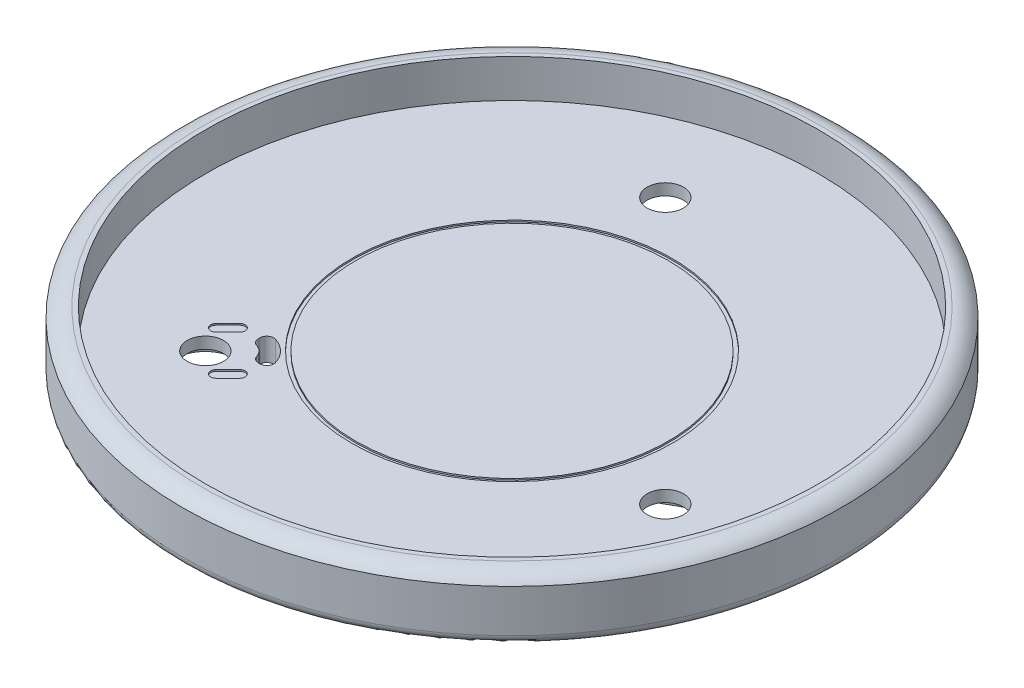
SolidWorks part; units mm, degrees
ref_plane "前视基准面" through (0, 0, 0) normal (0, 0, 1) x (1, 0, 0)
ref_plane "上视基准面" through (0, 0, 0) normal (0, 1, 0) x (1, 0, 0)
ref_plane "右视基准面" through (0, 0, 0) normal (1, 0, 0) x (0, 0, -1)
sketch "草图1" plane through (0, 0, 0) normal (0, 1, 0) x (1, 0, 0)
  circle A0 centre (0, 0) radius 40.2
  circle A1 centre (0, 0) radius 20.5 construction
  dimension "D1" = 80.4
  dimension "D2" = 41
extrude "凸台-拉伸1" add sketch "草图1" along normal blind 3
sketch "草图3" plane through (0, 0, 0) normal (0, -1, 0) x (1, 0, 0)
  circle A0 centre (0, 0) radius 43.2
  circle A1 centre (0, 0) radius 40.2 construction
  circle A2 centre (0, 0) radius 40.2
  dimension "D1" = 3
extrude "凸台-拉伸2" add sketch "草图3" against normal blind 8
sketch "草图4" plane through (0, 3, 0) normal (0, 1, 0) x (1, 0, 0)
  line L0 (-37.8336, 0) -> (34.4444, 0) construction
  line L1 (0, 37.4001) -> (0, -32.3556) construction
  circle A0 centre (0, 0) radius 20.5
  circle A1 centre (0, 0) radius 21
  dimension "D1" = 41
  dimension "D2" = 42
extrude "切除-拉伸1" cut sketch "草图4" against normal blind 0.2
sketch "草图5" plane through (0, 0, 0) normal (1, 0, 0) x (0, 0, -1)
  line L0 (43.2, 6.8) -> (43.2, 8)
  line L2 (43.2, 8) -> (40.8, 8)
  line L3 (40.2, 8) -> (-40.2, 8) construction
  line L4 (0, 0) -> (0, 12.9368)
  arc A0 (40.8, 8) -> (43.2, 6.8) centre (40.8, 5) cw
  dimension "D1" = 1.2
  dimension "D2" = 2.4
revolve "切除-旋转1" cut sketch "草图5" angle 360 about L4
fillet "圆角2" radius 1.2 1 edges at (0, 0, -43.2)
sketch "草图6" plane through (0, 0, 0) normal (0, -1, 0) x (1, 0, 0)
  line L0 (-29.5028, 0) -> (27.9284, 0) construction
  line L1 (0, 23.6501) -> (0, -22.1442) construction
  line L2 (-26, 23.2) -> (-23.8509, 18.3731)
  line L3 (-24, 26) -> (-18, 26)
  line L4 (-26, 24) -> (-26, 19)
  line L5 (-20.1967, 16) -> (-18, 16)
  line L6 (-16, 20.1967) -> (-16, 18)
  line L7 (-23.2, 26) -> (-18.3731, 23.8509)
  line L8 (33.0918, 10.9167) -> (27.837, 11.469)
  line L9 (33.7846, 10.5167) -> (29.4545, 13.0167)
  line L10 (34.5167, 7.7846) -> (31.5167, 2.5885)
  line L11 (34.1167, 7.0918) -> (29.842, 3.9861)
  line L12 (25.4909, 3.758) -> (23.5885, 4.8564)
  line L13 (23.9548, 9.4909) -> (22.8564, 7.5885)
  line L14 (-7.0918, -34.1167) -> (-3.9861, -29.842)
  line L15 (-7.7846, -34.5167) -> (-3.4545, -32.0167)
  line L16 (-10.5167, -33.7846) -> (-13.5167, -28.5885)
  line L17 (-10.9167, -33.0918) -> (-11.469, -27.837)
  line L18 (-9.4909, -23.9548) -> (-7.5885, -22.8564)
  line L19 (-3.758, -25.4909) -> (-4.8564, -23.5885)
  arc A0 (-26, 24) -> (-24, 26) centre (-24, 24) cw
  arc A1 (-18, 16) -> (-16, 18) centre (-18, 18) ccw
  arc A2 (-16, 20.1967) -> (-18.3731, 23.8509) centre (-20, 20.1967) ccw
  arc A3 (-23.8509, 18.3731) -> (-20.1967, 16) centre (-20.1967, 20) ccw
  arc A4 (33.7846, 10.5167) -> (34.5167, 7.7846) centre (32.7846, 8.7846) cw
  arc A5 (25.4909, 3.758) -> (29.842, 3.9861) centre (27.4909, 7.2221) ccw
  arc A6 (22.8564, 7.5885) -> (23.5885, 4.8564) centre (24.5885, 6.5885) ccw
  arc A7 (27.837, 11.469) -> (23.9548, 9.4909) centre (27.4189, 7.4909) ccw
  arc A8 (-7.7846, -34.5167) -> (-10.5167, -33.7846) centre (-8.7846, -32.7846) cw
  arc A9 (-9.4909, -23.9548) -> (-11.469, -27.837) centre (-7.4909, -27.4189) ccw
  arc A10 (-4.8564, -23.5885) -> (-7.5885, -22.8564) centre (-6.5885, -24.5885) ccw
  arc A11 (-3.9861, -29.842) -> (-3.758, -25.4909) centre (-7.2221, -27.4909) ccw
  point P11 (-26, 26)
  point P18 (-16, 16)
  point P58 (0, 0)
  dimension "D5" = 2
  dimension "D10" = 2
  dimension "D3" = 4
  dimension "D1" = 16
  dimension "D2" = 16
  dimension "D4" = 10
  dimension "D6" = 24
  dimension "D7" = 24
  dimension "D8" = 0.8
  dimension "D9" = 0.8
  dimension "D11" = 10
  dimension "D12" = 3
extrude "切除-拉伸2" cut sketch "草图6" against normal blind 1.5 contours L14 A11 L19 A10 L18 A9 L17 L16 A8 L15 | L8 A7 L13 A6 L12 A5 L11 L10 A4 L9 | L2 A3 L5 A1 L6 A2 L7 L3 A0 L4
sketch "草图7" plane through (0, 0, 0) normal (0, -1, 0) x (1, 0, 0)
  line L0 (0, 0) -> (-25.4142, 25.4142) construction
  line L1 (-18, 15.0335) -> (-18, 15.2432)
  line L2 (-15.0335, 18) -> (-15.2432, 18)
  arc A0 (-24, 26) -> (-26, 24) centre (-24, 24) ccw construction
  arc A3 (-18, 16) -> (-16, 18) centre (-18, 18) ccw construction
  arc A4 (-17.3793, 16.0988) -> (-16.0988, 17.3793) centre (-18, 18) ccw
  arc A5 (-16.8387, 14.1723) -> (-14.1723, 16.8387) centre (-18, 18) ccw
  arc A6 (-18, 16) -> (-16, 18) centre (-18, 18) ccw construction
  arc A7 (-18, 15.2432) -> (-17.3793, 16.0988) centre (-17.1, 15.2432) cw
  arc A8 (-18, 14) -> (-14, 18) centre (-18, 18) ccw construction
  arc A9 (-18, 15.0335) -> (-16.8387, 14.1723) centre (-17.1, 15.0335) ccw
  arc A10 (-14.1723, 16.8387) -> (-15.0335, 18) centre (-15.0335, 17.1) ccw
  arc A11 (-15.2432, 18) -> (-16.0988, 17.3793) centre (-15.2432, 17.1) ccw
  dimension "D2" = 0.9
  dimension "D1" = 2
extrude "切除-拉伸3" cut sketch "草图7" against normal blind 10
sketch "草图8" plane through (0, 3, 0) normal (0, 1, 0) x (1, 0, 0)
  line L0 (0, 0) -> (-24.3102, -24.3102) construction
  line L1 (-16.7808, -22.0134) -> (-15.2252, -20.4578) construction
  line L2 (-17.2758, -21.5184) -> (-15.7201, -19.9628)
  line L3 (-16.2858, -22.5084) -> (-14.7302, -20.9527)
  line L4 (-22.0134, -16.7808) -> (-20.4578, -15.2252) construction
  line L5 (-21.5184, -17.2758) -> (-19.9628, -15.7201)
  line L6 (-22.5084, -16.2858) -> (-20.9527, -14.7302)
  arc A0 (-17.2758, -21.5184) -> (-16.2858, -22.5084) centre (-16.7808, -22.0134) ccw
  arc A1 (-14.7302, -20.9527) -> (-15.7201, -19.9628) centre (-15.2252, -20.4578) ccw
  arc A2 (-16.0988, -17.3793) -> (-17.3793, -16.0988) centre (-18, -18) ccw construction
  arc A3 (-16.0988, -17.3793) -> (-17.3793, -16.0988) centre (-18, -18) ccw
  arc A4 (-21.5184, -17.2758) -> (-22.5084, -16.2858) centre (-22.0134, -16.7808) cw
  arc A5 (-20.9527, -14.7302) -> (-19.9628, -15.7201) centre (-20.4578, -15.2252) cw
  point P5 (-16.003, -21.2356)
  point P16 (-21.2356, -16.003)
  dimension "D2" = 0.7
  dimension "D1" = 2.2
  dimension "D3" = 3
  dimension "D4" = 3.2
extrude "切除-拉伸4" cut sketch "草图8" against normal blind 0.2 contours A5 L6 A4 L5 | L3 A1 L2 A0
sketch "草图9" plane through (0, 3, 0) normal (0, 1, 0) x (1, 0, 0)
  line L0 (-20, -20.1967) -> (-20.1967, -20)
  line L1 (0, 0) -> (-20.0984, -20.0984) construction
  circle A0 centre (-20.0984, -20.0984) radius 2.38
  circle A1 centre (-7.3565, 27.4549) radius 2.38
  circle A2 centre (27.4549, -7.3565) radius 2.38
  dimension "D1" = 4.76
  dimension "D3" = 28.4234
  dimension "D2" = 3
extrude "切除-拉伸5" cut sketch "草图9" against normal blind 10
sketch "草图10" plane through (0, 0, 0) normal (0, -1, 0) x (1, 0, 0)
  line L0 (0, 0) -> (-15.1716, 15.1716) construction
  line L1 (-21.7279, -6.5563) -> (6.5563, 21.7279) construction
  arc A0 (-16.8387, 14.1723) -> (-14.1723, 16.8387) centre (-18, 18) ccw construction
  text T0 "<b>08</b>" font "JetBrains Mono" height 9
  point P10 (-7.5858, 7.5858)
  dimension "D1" = 20
  dimension "D2" = 40
extrude "切除-拉伸6" cut sketch "草图10" against normal blind 0.8
